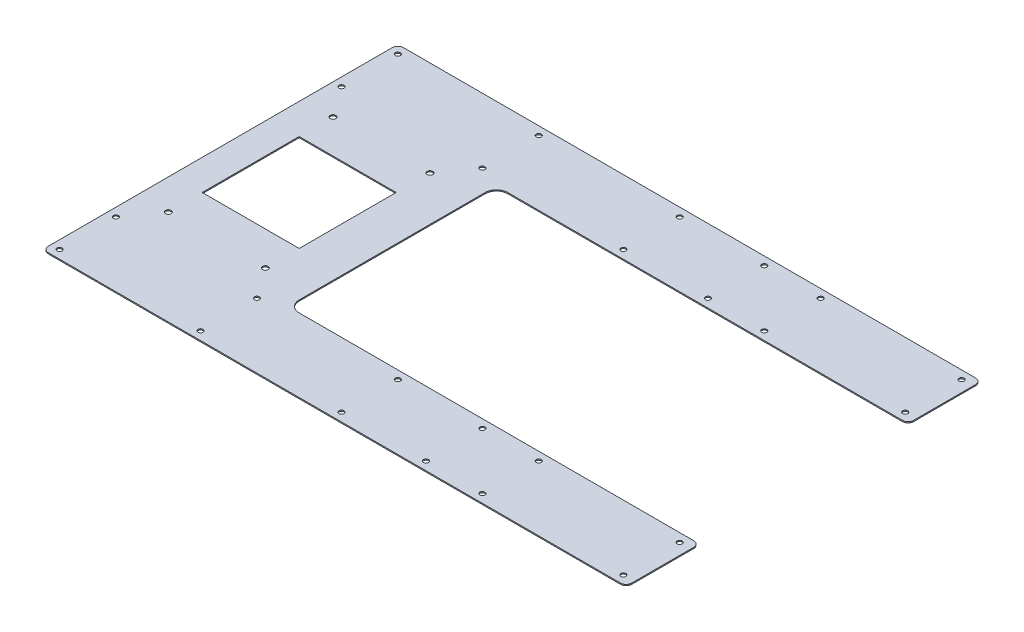
SolidWorks part; units mm, degrees
ref_plane "Front Plane" through (0, 0, 0) normal (0, 0, 1) x (1, 0, 0)
ref_plane "Top Plane" through (0, 0, 0) normal (0, 1, 0) x (1, 0, 0)
ref_plane "Right Plane" through (0, 0, 0) normal (1, 0, 0) x (0, 0, -1)
sketch "Sketch1" plane through (0, 0, 0) normal (0, 1, 0) x (1, 0, 0)
  line L0 (-62.5, 100) -> (-62.5, -100) construction
  line L1 (-34.8, 34.8) -> (34.8, 34.8) construction
  line L2 (-34.8, 34.8) -> (-34.8, -34.8) construction
  line L3 (-34.8, -34.8) -> (34.8, -34.8) construction
  line L4 (34.8, 34.8) -> (34.8, -34.8) construction
  line L5 (-34.8, 34.8) -> (34.8, -34.8) construction
  line L6 (-34.8, -34.8) -> (34.8, 34.8) construction
  line L7 (-43, 43) -> (43, 43)
  line L8 (-43, 43) -> (-43, -43)
  line L9 (-43, -43) -> (43, -43)
  line L10 (43, 43) -> (43, -43)
  line L11 (-43, 43) -> (43, -43) construction
  line L12 (-43, -43) -> (43, 43) construction
  line L13 (-62.5, -100) -> (312.5, -100) construction
  line L14 (312.5, -100) -> (312.5, 100) construction
  line L15 (312.5, 100) -> (-62.5, 100) construction
  line L16 (-62.5, 0) -> (0, 0) construction
  line L17 (0, 0) -> (312.5, 0) construction
  line L18 (-62.5, 100) -> (-62.5, 150) construction
  line L19 (262.5, 150) -> (262.5, -150) construction
  line L20 (-70, -157.5) -> (447.5, -157.5)
  line L21 (-62.5, -150) -> (-62.5, -100) construction
  line L22 (-70, -157.5) -> (-70, 157.5)
  line L23 (-70, 157.5) -> (447.5, 157.5)
  line L24 (447.5, -157.5) -> (447.5, -92.5)
  line L25 (-70, -157.5) -> (447.5, 157.5) construction
  line L26 (-70, 157.5) -> (447.5, -157.5) construction
  line L27 (-43, 73) -> (43, 73) construction
  line L28 (-43, 73) -> (-43, -73) construction
  line L29 (-43, -73) -> (43, -73) construction
  line L30 (43, 73) -> (43, -73) construction
  line L31 (-43, 73) -> (43, -73) construction
  line L32 (-43, -73) -> (43, 73) construction
  line L33 (262.5, -150) -> (312.5, -150) construction
  line L34 (447.5, 92.5) -> (82.5, 92.5)
  line L35 (262.5, 150) -> (312.5, 150) construction
  line L36 (82.5, 92.5) -> (82.5, -92.5)
  line L37 (82.5, -92.5) -> (447.5, -92.5)
  line L38 (447.5, 92.5) -> (447.5, 157.5)
  line L39 (447.5, 92.5) -> (447.5, -92.5) construction
  line L40 (312.5, 0) -> (447.5, 0) construction
  line L41 (62.5, 100) -> (62.5, -100) construction
  circle A0 centre (0, 0) radius 36.5 construction
  circle A1 centre (-34.8, 34.8) radius 3.45 construction
  circle A2 centre (34.8, 34.8) radius 3.45 construction
  circle A3 centre (34.8, -34.8) radius 3.45 construction
  circle A4 centre (-34.8, -34.8) radius 3.45 construction
  circle A5 centre (0, 0) radius 7.5
  circle A6 centre (-62.5, 100) radius 2.25
  circle A7 centre (-62.5, -100) radius 2.25
  circle A8 centre (-62.5, 150) radius 2.25
  circle A9 centre (-62.5, -150) radius 2.25
  circle A10 centre (62.5, -100) radius 2.25
  circle A11 centre (62.5, -150) radius 2.25
  circle A12 centre (62.5, 100) radius 2.25
  circle A13 centre (62.5, 150) radius 2.25
  circle A14 centre (187.5, -100) radius 2.25
  circle A15 centre (187.5, -150) radius 2.25
  circle A16 centre (187.5, 100) radius 2.25
  circle A17 centre (187.5, 150) radius 2.25
  circle A18 centre (312.5, -100) radius 2.25
  circle A19 centre (312.5, -150) radius 2.25
  circle A20 centre (312.5, 100) radius 2.25
  circle A21 centre (312.5, 150) radius 2.25
  circle A22 centre (437.5, -100) radius 2.25
  circle A23 centre (437.5, -150) radius 2.25
  circle A24 centre (437.5, 100) radius 2.25
  circle A25 centre (437.5, 150) radius 2.25
  circle A26 centre (-43, -73) radius 2.5
  circle A27 centre (43, -73) radius 2.5
  circle A30 centre (-43, 73) radius 2.5
  circle A31 centre (43, 73) radius 2.5
  circle A34 centre (262.5, 150) radius 2.25
  circle A35 centre (262.5, 100) radius 2.25
  circle A36 centre (262.5, -100) radius 2.25
  circle A37 centre (262.5, -150) radius 2.25
  point P0 (0, 0)
  point P21 (188.75, 0)
  point P30 (-70, 0)
  dimension "D1" = 69.6
  dimension "D2" = 6.9
  dimension "D3" = 73
  dimension "D4" = 15
  dimension "D8" = 50
  dimension "D9" = 4.5
  dimension "D17" = 5
  dimension "D19" = 20
  dimension "D5" = 86
  dimension "D6" = 200
  dimension "D7" = 62.5
  dimension "D11" = 125
  dimension "D12" = 7.5
  dimension "D13" = 10
  dimension "D14" = 7.5
  dimension "D15" = 86
  dimension "D16" = 30
  dimension "D18" = 50
  dimension "D20" = 7.5
  dimension "D10" = 5
extrude "Boss-Extrude1" add sketch "Sketch1" along normal blind 1 contours L20 L24 L23 L22 A31 A30 A27 A26 A21 A20 A19 A18 A17 A16 A15 A14 A13 A12 A11 A10 A9 A8 A7 A6 L7 L10 L9 L8
fillet "Fillet1" radius 5 6 edges at (447.5, 0.5, 157.5) (-70, 0.5, 157.5) (-70, 0.5, -157.5) (447.5, 0.5, 92.5) (447.5, 0.5, -92.5) (447.5, 0.5, -157.5)
fillet "Fillet2" radius 10 2 edges at (82.5, 0.5, -92.5) (82.5, 0.5, 92.5)
